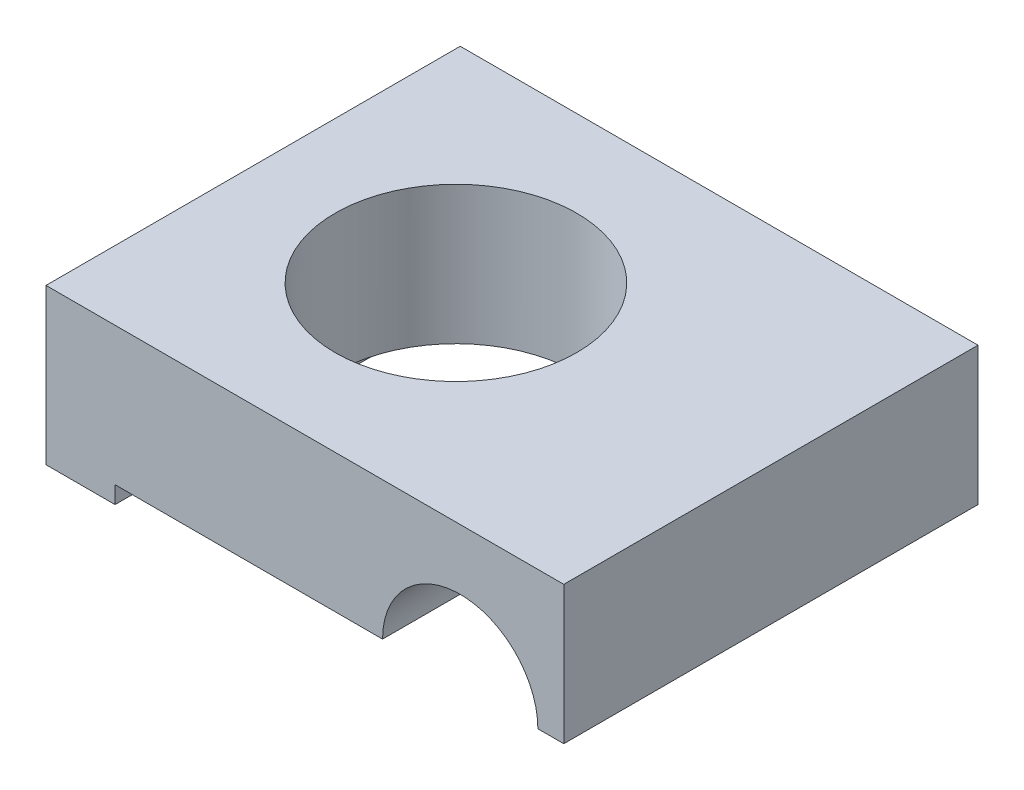
SolidWorks part; units mm, degrees
material "AISI 1020"
ref_plane "Plano frontal" through (0, 0, 0) normal (0, 0, 1) x (1, 0, 0)
ref_plane "Plano superior" through (0, 0, 0) normal (0, 1, 0) x (1, 0, 0)
ref_plane "Plano direito" through (0, 0, 0) normal (1, 0, 0) x (0, 0, -1)
sketch "Esboço1" plane through (0, 0, 0) normal (0, 0, 1) x (1, 0, 0)
  line L0 (0, 0) -> (-12, 0)
  line L1 (-12, 0) -> (-12, 4)
  line L2 (-12, 4) -> (3, 4)
  line L3 (3, 4) -> (3, 0)
  line L4 (3, 0) -> (0, 0)
  line L6 (-12, 0) -> (-10, 0)
  line L7 (-12, 0) -> (-12, -0.5)
  line L8 (-12, -0.5) -> (-10, -0.5)
  line L9 (-10, 0) -> (-10, -0.5)
  circle A0 centre (0, 0) radius 2.25
  dimension "D1" = 4.5
  dimension "D2" = 4
  dimension "D3" = 12
  dimension "D4" = 2
  dimension "D5" = 0.5
  dimension "D6" = 3
extrude "Extrusão1" add sketch "Esboço1" along normal mid plane 12 contours A0 L4 L3 L2 L1 L0 | L9 L0 L7 L8
sketch "Esboço2" plane through (0, 0, 0) normal (0, -1, 0) x (1, 0, 0)
  line L0 (-2.25, 6) -> (-10, -6) construction
  circle A0 centre (-6.125, 0) radius 3.5
  dimension "D1" = 7
extrude "Corte-extrusão1" cut sketch "Esboço2" against normal blind 12
